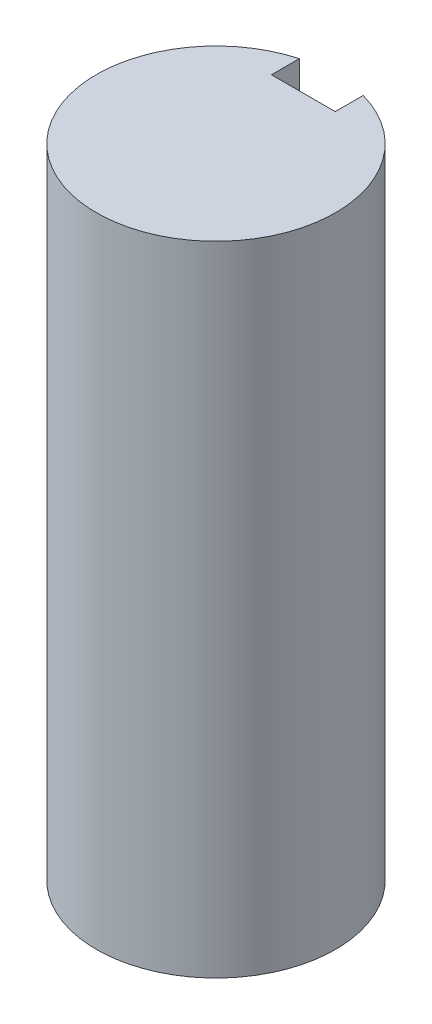
SolidWorks part; units mm, degrees
ref_plane "Front Plane" through (0, 0, 0) normal (0, 0, 1) x (1, 0, 0)
ref_plane "Top Plane" through (0, 0, 0) normal (0, 1, 0) x (1, 0, 0)
ref_plane "Right Plane" through (0, 0, 0) normal (1, 0, 0) x (0, 0, -1)
sketch "Sketch1" plane through (0, 0, 0) normal (0, 1, 0) x (1, 0, 0)
  circle A0 centre (0, 0) radius 15
extrude "Boss-Extrude1" add sketch "Sketch1" along normal blind 80
sketch "Sketch2" plane through (0, 80, 0) normal (0, 1, 0) x (1, 0, 0)
  line L0 (0, 38.8943) -> (0, -16.9806) construction
  line L2 (-4, 14.4568) -> (4, 14.4568)
  line L3 (-4, 14.4568) -> (-4, 10.9568)
  line L4 (-4, 10.9568) -> (4, 10.9568)
  line L5 (4, 14.4568) -> (4, 10.9568)
  circle A0 centre (0, 0) radius 15 construction
  point P7 (0, 0)
  point P10 (0, 0)
  point P11 (0, 10.9568)
  dimension "D1" = 3.5
  dimension "D2" = 8
extrude "Cut-Extrude2" cut sketch "Sketch2" against normal through all contours L3 L2 L5 L4
sketch "Sketch5" plane through (0, 80, 0) normal (0, 1, 0) x (1, 0, 0)
  line L1 (-4, 14.4568) -> (4.4676, 14.4568)
  line L2 (-4, 14.4568) -> (-4, 15.3905)
  line L3 (-4, 15.3905) -> (4.4676, 15.3905)
  line L4 (4.4676, 14.4568) -> (4.4676, 15.3905)
extrude "Cut-Extrude3" cut sketch "Sketch5" against normal through all
